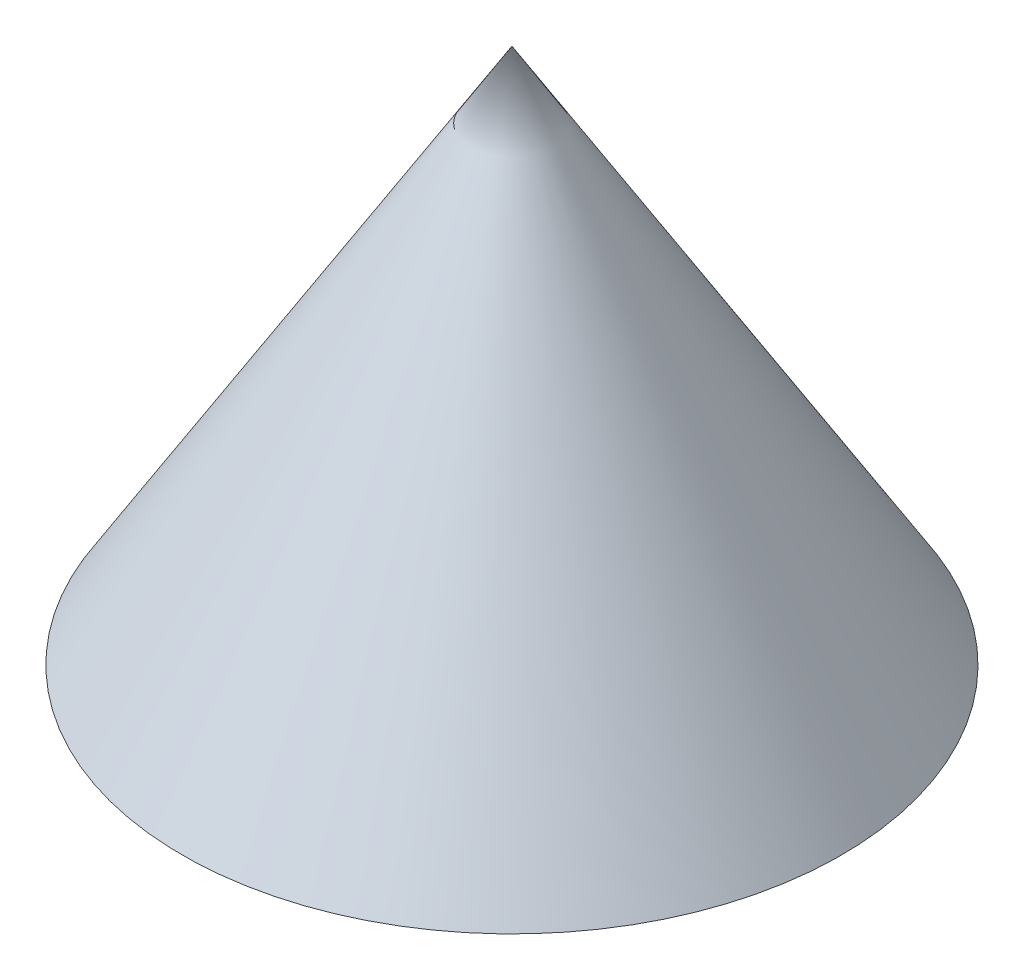
SolidWorks part; units mm, degrees
ref_plane "Front Plane" through (0, 0, 0) normal (0, 0, 1) x (1, 0, 0)
ref_plane "Top Plane" through (0, 0, 0) normal (0, 1, 0) x (1, 0, 0)
ref_plane "Right Plane" through (0, 0, 0) normal (1, 0, 0) x (0, 0, -1)
sketch "Sketch1" plane through (0, 0, 0) normal (0, 0, 1) x (1, 0, 0)
  line L0 (0, 0) -> (0, 43.5637)
  line L1 (0, 43.5637) -> (26.7958, 0)
  line L2 (26.7958, 0) -> (0, 0)
revolve "Revolve1" add sketch "Sketch1" angle 360 about L0
ref_point "Point1"
